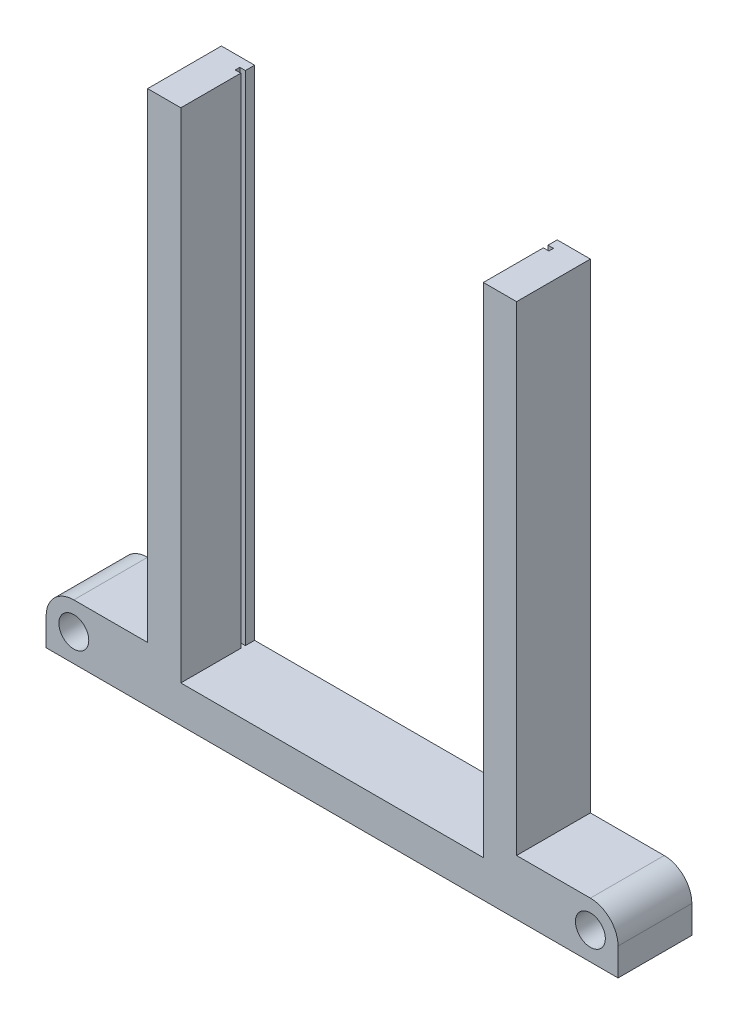
SolidWorks part; units mm, degrees
material "ABS"
ref_plane "Front Plane" through (0, 0, 0) normal (0, 0, 1) x (1, 0, 0)
ref_plane "Top Plane" through (0, 0, 0) normal (0, 1, 0) x (1, 0, 0)
ref_plane "Right Plane" through (0, 0, 0) normal (1, 0, 0) x (0, 0, -1)
sketch "Sketch1" plane through (0, 0, 0) normal (0, 0, 1) x (1, 0, 0)
  line L0 (-77.5, 0) -> (77.5, 0)
  line L1 (-70, 7.5) -> (70, 7.5) construction
  line L2 (-77.5, 0) -> (-77.5, 7.5)
  line L3 (-70, 15) -> (-50, 15)
  line L4 (-50, 15) -> (-50, 145)
  line L5 (-50, 145) -> (50, 145)
  line L6 (50, 145) -> (50, 15)
  line L7 (50, 15) -> (70, 15)
  line L8 (77.5, 7.5) -> (77.5, 0)
  circle A0 centre (-70, 7.5) radius 4.05
  circle A1 centre (70, 7.5) radius 4.05
  arc A2 (-77.5, 7.5) -> (-70, 15) centre (-70, 7.5) cw
  arc A3 (70, 15) -> (77.5, 7.5) centre (70, 7.5) cw
  point P2 (0, 0)
  point P6 (0, 145)
  point P8 (0, 7.5)
  dimension "D2" = 8.1
  dimension "D1" = 140
  dimension "D3" = 155
  dimension "D4" = 7.5
  dimension "D5" = 130
  dimension "D6" = 100
extrude "Boss-Extrude1" add sketch "Sketch1" along normal mid plane 20 contours L4 L5 L6 L7 A3 L8 L0 L2 A2 L3
sketch "Sketch2" plane through (0, 145, 0) normal (0, 1, 0) x (1, 0, 0)
  line L0 (-41, -10) -> (-41, 6.25)
  line L1 (50, -10) -> (-50, -10) construction
  line L2 (-41, 6.25) -> (-42.5, 6.25)
  line L3 (-42.5, 6.25) -> (-42.5, 7.5)
  line L4 (-42.5, 7.5) -> (-41, 7.5)
  line L5 (-41, 7.5) -> (-41, 10)
  line L6 (50, 10) -> (-50, 10) construction
  line L7 (-41, 10) -> (41, 10)
  line L8 (41, 10) -> (41, 7.5)
  line L9 (41, 7.5) -> (42.5, 7.5)
  line L10 (42.5, 7.5) -> (42.5, 6.25)
  line L11 (42.5, 6.25) -> (41, 6.25)
  line L12 (41, 6.25) -> (41, -10)
  line L13 (41, -10) -> (-41, -10)
  point P6 (0, 10)
  dimension "D1" = 1.25
  dimension "D2" = 85
  dimension "D3" = 82
  dimension "D4" = 2.5
extrude "Cut-Extrude1" cut sketch "Sketch2" against normal offset from surface (135 mm away) 10 up to face at (0, 0, 0)
